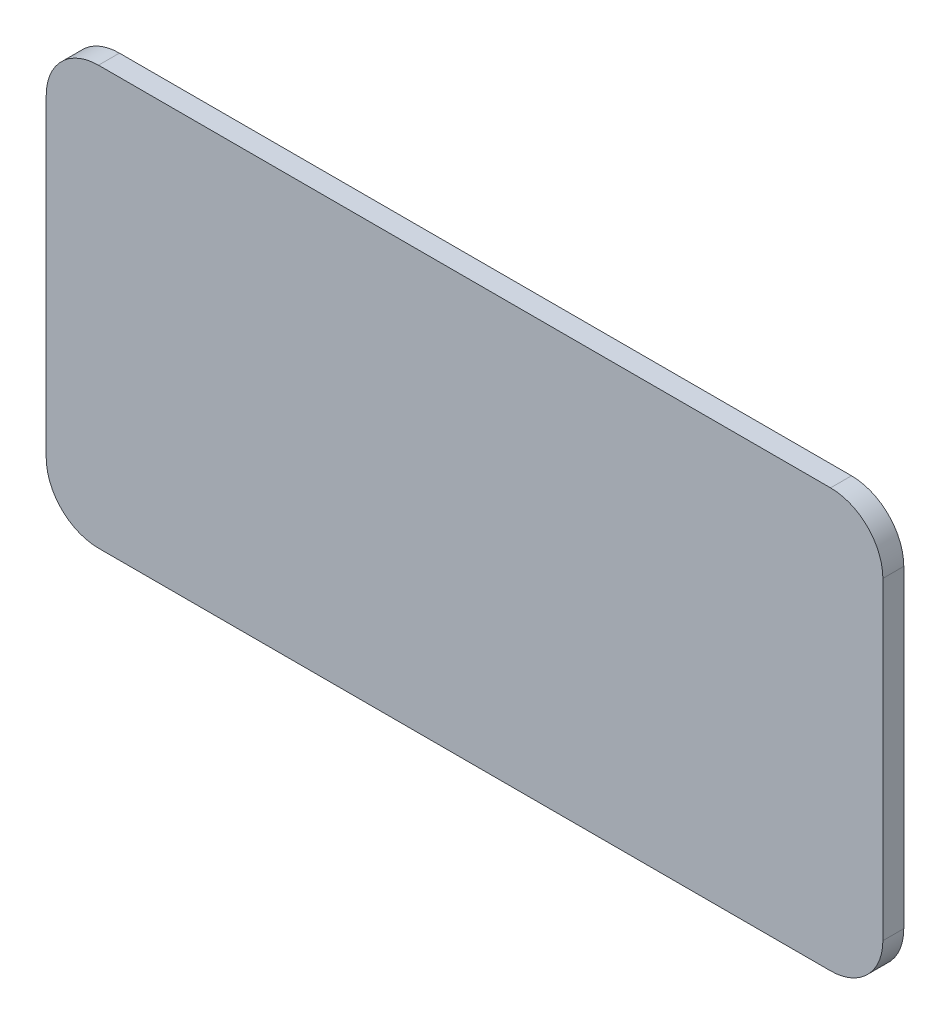
SolidWorks part; units mm, degrees
material "AISI 304"
ref_plane "Спереди" through (0, 0, 0) normal (0, 0, 1) x (1, 0, 0)
ref_plane "Сверху" through (0, 0, 0) normal (0, 1, 0) x (1, 0, 0)
ref_plane "Справа" through (0, 0, 0) normal (1, 0, 0) x (0, 0, -1)
sketch "Эскиз1" plane through (0, 0, 0) normal (0, 0, 1) x (1, 0, 0)
  line L1 (-35, -20) -> (35, -20)
  line L2 (-40, -15) -> (-40, 20)
  line L3 (-40, 20) -> (40, 20)
  line L4 (40, -15) -> (40, 20)
  line L5 (-40, -20) -> (40, 20) construction
  line L6 (-40, 20) -> (40, -20) construction
  arc A0 (35, -20) -> (40, -15) centre (35, -15) ccw
  arc A1 (-35, -20) -> (-40, -15) centre (-35, -15) cw
  point P0 (0, 0)
  dimension "D3" = 5
  dimension "D1" = 40
  dimension "D2" = 80
extrude "Бобышка-Вытянуть1" add sketch "Эскиз1" along normal blind 2
fillet "Скругление1" radius 5 2 edges at (40, 20, 1) (-40, 20, 1)
